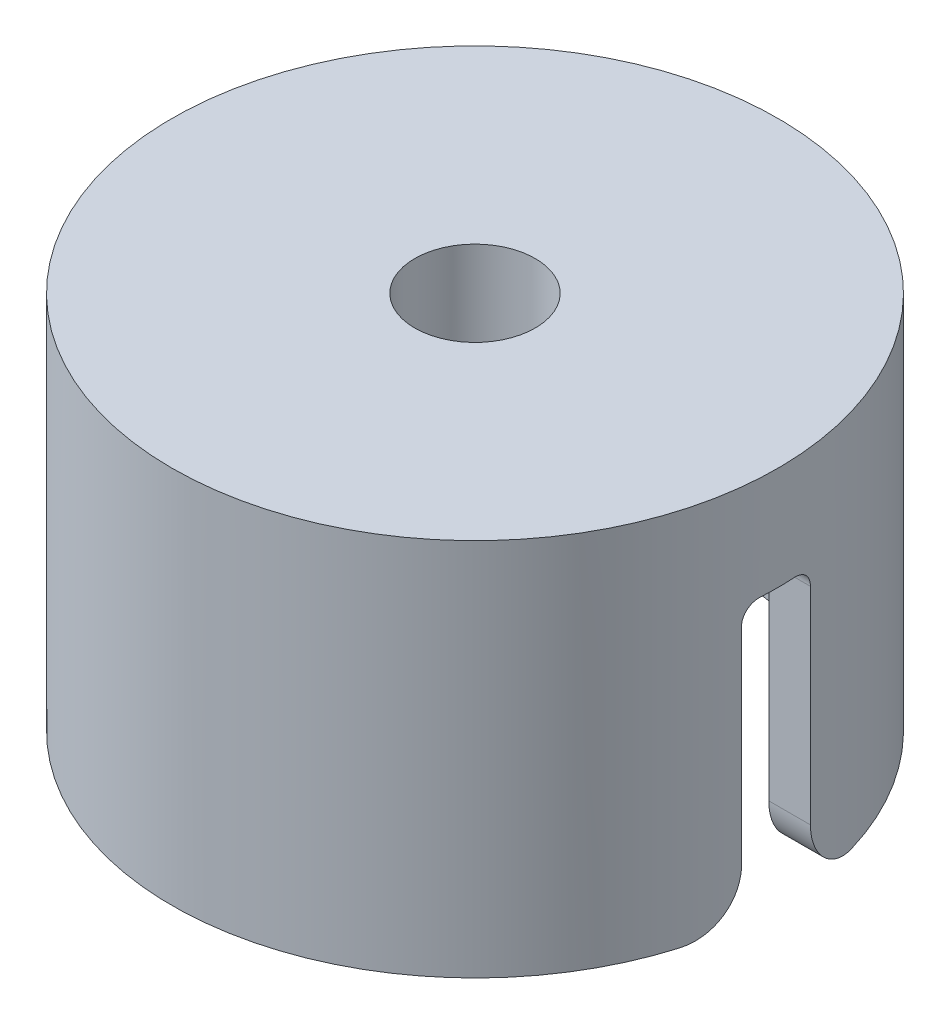
SolidWorks part; units mm, degrees
ref_plane "Front Plane" through (0, 0, 0) normal (0, 0, 1) x (1, 0, 0)
ref_plane "Top Plane" through (0, 0, 0) normal (0, 1, 0) x (1, 0, 0)
ref_plane "Right Plane" through (0, 0, 0) normal (1, 0, 0) x (0, 0, -1)
sketch "Sketch1" plane through (0, 0, 0) normal (0, 1, 0) x (1, 0, 0)
  circle A0 centre (0, 0) radius 7.6
  circle A1 centre (0, 0) radius 8.8
  dimension "D1" = 17.6
  dimension "D2" = 1.2
extrude "Boss-Extrude1" add sketch "Sketch1" along normal blind 10
sketch "Sketch2" plane through (0, 0, 0) normal (0, -1, 0) x (1, 0, 0)
  line L1 (-18.1717, -1) -> (18.1717, -1) construction
  line L2 (-18.1717, -1) -> (-18.1717, 1) construction
  line L3 (-18.1717, 1) -> (18.1717, 1) construction
  line L4 (18.1717, -1) -> (18.1717, 1) construction
  line L5 (-18.1717, -1) -> (18.1717, 1) construction
  line L6 (-18.1717, 1) -> (18.1717, -1) construction
  line L7 (18.1717, 1) -> (0, 1)
  line L8 (18.1717, 1) -> (18.1717, -1)
  line L9 (18.1717, -1) -> (0, -1)
  line L10 (0, 1) -> (0, -1)
  point P0 (0, 0)
  dimension "D1" = 2
extrude "Cut-Extrude1" cut sketch "Sketch2" against normal blind 8
sketch "Sketch3" plane through (0, 10, 0) normal (0, 1, 0) x (1, 0, 0)
  circle A0 centre (0, 0) radius 8.8
  circle A1 centre (0, 0) radius 8.8 construction
extrude "Boss-Extrude2" add sketch "Sketch3" along normal blind 1
sketch "Sketch4" plane through (0, 11, 0) normal (0, 1, 0) x (1, 0, 0)
  circle A0 centre (0, 0) radius 1.75
  dimension "D1" = 3.5
extrude "Cut-Extrude2" cut sketch "Sketch4" against normal through all
fillet "Fillet1" radius 0.5 2 edges at (8.1385, 8, 1) (8.1385, 8, -1)
fillet "Fillet3" radius 1.5 2 edges at (8.1385, 0, -1) (8.1385, 0, 1)
pattern_circular "CirPattern1" count 2 over 360 of "Cut-Extrude1", "Fillet1", "Fillet3"
sketch "Sketch5" plane through (0, 10, 0) normal (0, -1, 0) x (1, 0, 0)
  circle A0 centre (0, 0) radius 1.75
  circle A1 centre (0, 0) radius 2.95
  dimension "D1" = 3.5
  dimension "D2" = 1.2
extrude "Boss-Extrude3" add sketch "Sketch5" along normal blind 3
sketch "Sketch6" [suppressed] plane through (0, 0, 0) normal (0, -1, 0) x (1, 0, 0)
  line L0 (0, 12.0609) -> (0, 5.202)
  line L1 (18.7743, 12.0609) -> (0, 12.0609)
  line L2 (18.7743, 12.0609) -> (18.7743, -11.176)
  line L3 (18.7743, -11.176) -> (0, -11.176)
  line L4 (0, 12.0609) -> (0, -11.176) construction
  line L5 (0, -5.202) -> (0, -11.176)
  circle A0 centre (0, 0) radius 5.202 construction
  arc A1 (0, 5.202) -> (0, -5.202) centre (0, 0) cw
extrude "Cut-Extrude4" [suppressed] cut sketch "Sketch6" against normal up to vertex
fillet "Fillet4" [suppressed] radius 1
sketch "Sketch7" [suppressed] plane through (0, 0, 0) normal (0, -1, 0) x (1, 0, 0)
  line L1 (6, 0) -> (11.8772, 0)
  line L2 (0, 6) -> (0, 12.3748)
  line L3 (0, 12.3748) -> (11.8772, 12.3748)
  line L4 (11.8772, 0) -> (11.8772, 12.3748)
  line L5 (-6, 0) -> (-12.1174, 0)
  line L6 (0, -6) -> (0, -12.6126)
  line L7 (0, -12.6126) -> (-12.1174, -12.6126)
  line L8 (-12.1174, 0) -> (-12.1174, -12.6126)
  arc A0 (0, -6) -> (6, 0) centre (0, 0) ccw
  arc A1 (0, 6) -> (-6, 0) centre (0, 0) ccw
  circle A2 centre (0, 0) radius 3.95
  circle A3 centre (0, 0) radius 2.95 construction
  dimension "D1" = 6
  dimension "D2" = 1
extrude "Cut-Extrude5" [suppressed] cut sketch "Sketch7" against normal blind 8
fillet "Fillet5" [suppressed] radius 1
fillet "Fillet6" radius 1 1 edges at (0, 10, 7.6)
